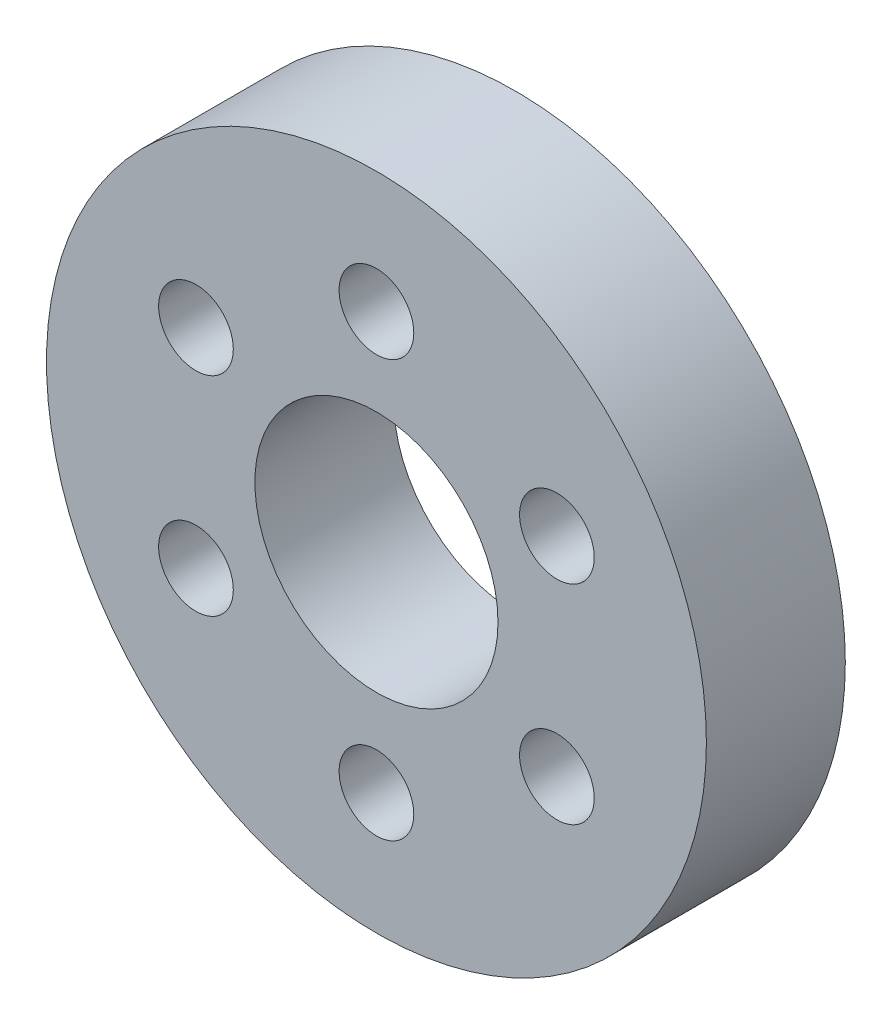
SolidWorks part; units mm, degrees
ref_plane "前视基准面" through (0, 0, 0) normal (0, 0, 1) x (1, 0, 0)
ref_plane "上视基准面" through (0, 0, 0) normal (0, 1, 0) x (1, 0, 0)
ref_plane "右视基准面" through (0, 0, 0) normal (1, 0, 0) x (0, 0, -1)
other "Configuration Table"
sketch "草图1" plane through (0, 0, 0) normal (0, 0, 1) x (1, 0, 0)
  circle A0 centre (0, -1.4874) radius 19
  circle A1 centre (0, -1.4874) radius 12 construction
  circle A2 centre (0, -1.4874) radius 7
  circle A3 centre (0, 10.5126) radius 2.15
  circle A4 centre (10.3923, 4.5126) radius 2.15
  circle A5 centre (10.3923, -7.4874) radius 2.15
  circle A6 centre (0, -13.4874) radius 2.15
  circle A7 centre (-10.3923, -7.4874) radius 2.15
  circle A8 centre (-10.3923, 4.5126) radius 2.15
  dimension "D1" = 6
extrude "凸台-拉伸1" add sketch "草图1" along normal blind 8
